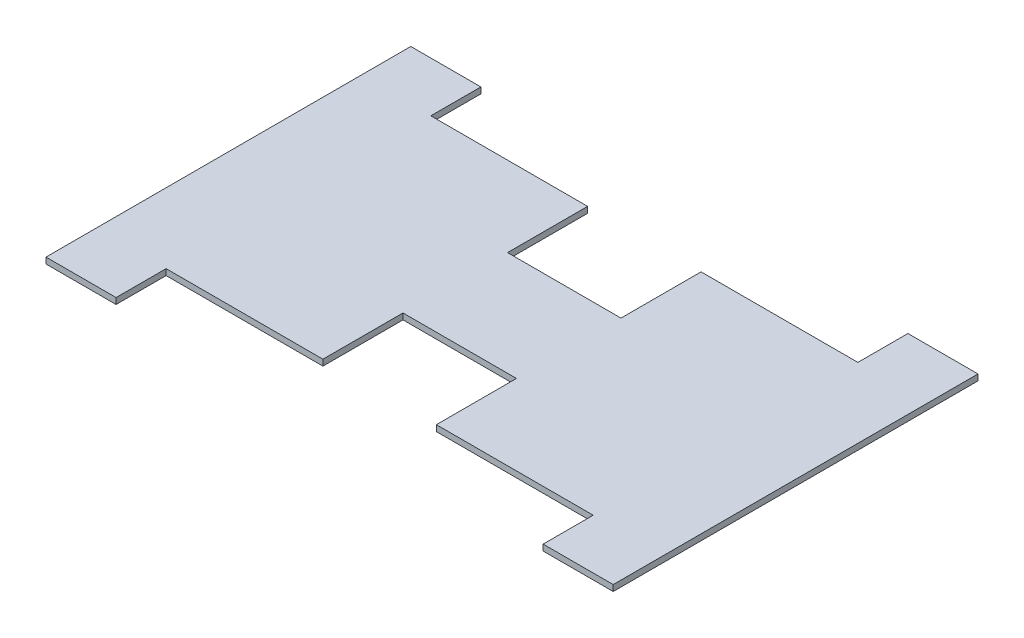
SolidWorks part; units mm, degrees
material "ABS PC"
ref_plane "Front Plane" through (0, 0, 0) normal (0, 0, 1) x (1, 0, 0)
ref_plane "Top Plane" through (0, 0, 0) normal (0, 1, 0) x (1, 0, 0)
ref_plane "Right Plane" through (0, 0, 0) normal (1, 0, 0) x (0, 0, -1)
sketch "Sketch1" plane through (0, 0, 0) normal (0, 1, 0) x (1, 0, 0)
  line L0 (-304.8, 260.35) -> (-304.8, 188.9125)
  line L1 (-404.8125, -260.35) -> (-304.8, -260.35)
  line L2 (-404.8125, -260.35) -> (-404.8125, 260.35)
  line L3 (-404.8125, 260.35) -> (-304.8, 260.35)
  line L4 (404.8125, -260.35) -> (404.8125, 260.35)
  line L5 (-80.9625, -74.6125) -> (80.9625, -74.6125)
  line L6 (-80.9625, -188.9125) -> (-80.9625, -74.6125)
  line L7 (-304.8, 188.9125) -> (-80.9625, 188.9125)
  line L8 (-80.9625, 188.9125) -> (-80.9625, 74.6125)
  line L9 (-80.9625, 74.6125) -> (80.9625, 74.6125)
  line L10 (0, 227.0125) -> (0, -227.0125) construction
  line L11 (-404.8125, 0) -> (404.8125, 0) construction
  line L12 (-304.8, -188.9125) -> (-80.9625, -188.9125)
  line L13 (-304.8, -260.35) -> (-304.8, -188.9125)
  line L14 (304.8, -260.35) -> (304.8, -188.9125)
  line L15 (304.8, -188.9125) -> (80.9625, -188.9125)
  line L16 (80.9625, 188.9125) -> (80.9625, 74.6125)
  line L17 (304.8, 188.9125) -> (80.9625, 188.9125)
  line L18 (80.9625, -188.9125) -> (80.9625, -74.6125)
  line L19 (304.8, 260.35) -> (304.8, 188.9125)
  line L20 (304.8, 260.35) -> (404.8125, 260.35)
  line L21 (304.8, -260.35) -> (404.8125, -260.35)
  point P0 (0, 0)
  point P18 (0, 0)
  point P29 (0, 74.6125)
  point P32 (0, -74.6125)
  dimension "D1" = 809.625
  dimension "D2" = 520.7
  dimension "D3" = 609.6
  dimension "D4" = 114.3
  dimension "D5" = 71.4375
  dimension "D6" = 161.925
extrude "Boss-Extrude1" add sketch "Sketch1" along normal blind 8.636
